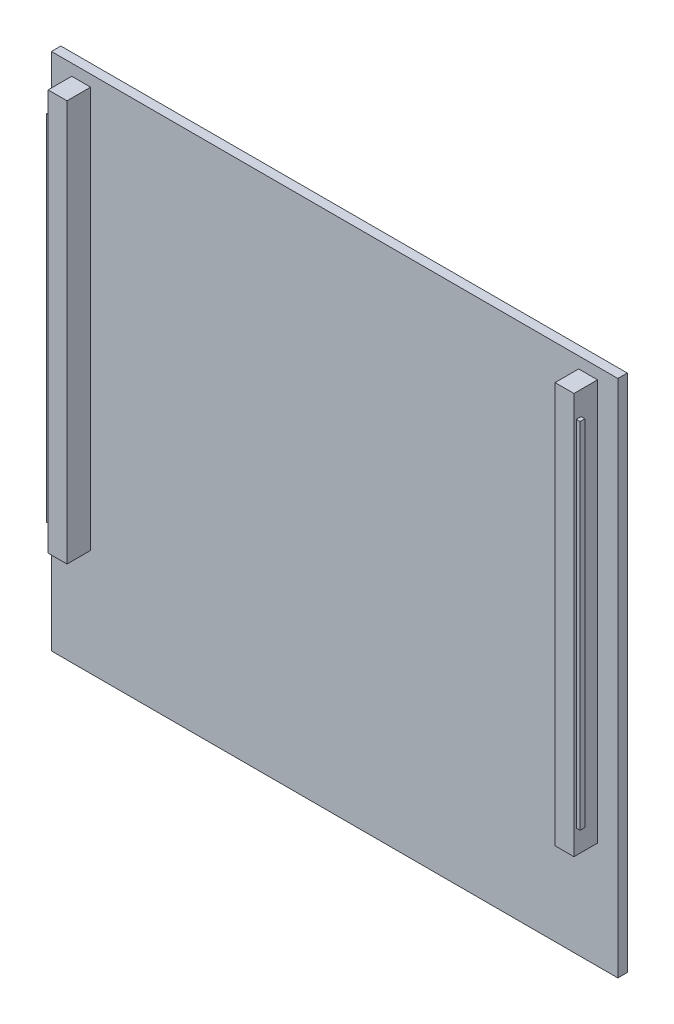
SolidWorks part; units mm, degrees
ref_plane "Ebene vorne" through (0, 0, 0) normal (0, 0, 1) x (1, 0, 0)
ref_plane "Ebene oben" through (0, 0, 0) normal (0, 1, 0) x (1, 0, 0)
ref_plane "Ebene rechts" through (0, 0, 0) normal (1, 0, 0) x (0, 0, -1)
sketch "Skizze1" plane through (0, 0, 0) normal (0, 0, 1) x (1, 0, 0)
  line L1 (-57.6339, 56.1305) -> (62.3661, 56.1305)
  line L2 (-57.6339, 56.1305) -> (-57.6339, -53.8695)
  line L3 (-57.6339, -53.8695) -> (62.3661, -53.8695)
  line L4 (62.3661, 56.1305) -> (62.3661, -53.8695)
  dimension "D1" = 120
  dimension "D2" = 110
extrude "Aufsatz-Linear austragen1" add sketch "Skizze1" along normal blind 2
sketch "Skizze2" plane through (0, 0, 2) normal (0, 0, 1) x (1, 0, 0)
  line L0 (62.3661, 56.1305) -> (-57.6339, 56.1305) construction
  line L1 (-53.3339, 53.7305) -> (-49.3339, 53.7305)
  line L2 (-53.3339, 53.7305) -> (-53.3339, -31.2695)
  line L3 (-53.3339, -31.2695) -> (-49.3339, -31.2695)
  line L4 (-49.3339, 53.7305) -> (-49.3339, -31.2695)
  line L5 (58.0661, 53.7305) -> (54.0661, 53.7305)
  line L6 (58.0661, 53.7305) -> (58.0661, -31.2695)
  line L7 (58.0661, -31.2695) -> (54.0661, -31.2695)
  line L8 (54.0661, 53.7305) -> (54.0661, -31.2695)
  line L9 (-57.6339, 56.1305) -> (-57.6339, -53.8695) construction
  line L10 (62.3661, -53.8695) -> (62.3661, 56.1305) construction
  dimension "D1" = 2.4
  dimension "D2" = 2.4
  dimension "D3" = 85
  dimension "D4" = 85
  dimension "D5" = 4
  dimension "D6" = 4
  dimension "D7" = 4.3
  dimension "D8" = 4.3
extrude "Aufsatz-Linear austragen2" add sketch "Skizze2" along normal blind 5
sketch "Skizze3" plane through (58.0661, 0, 0) normal (1, 0, 0) x (0, 0, -1)
  line L0 (-7, -31.2695) -> (-7, 53.7305) construction
  line L1 (-6.5, 48.7305) -> (-5.5, 48.7305)
  line L2 (-6.5, 48.7305) -> (-6.5, -26.2695)
  line L3 (-6.5, -26.2695) -> (-5.5, -26.2695)
  line L4 (-5.5, 48.7305) -> (-5.5, -26.2695)
  line L5 (-7, 53.7305) -> (-2, 53.7305) construction
  dimension "D1" = 1
  dimension "D2" = 0.5
  dimension "D3" = 5
  dimension "D4" = 75
extrude "Aufsatz-Linear austragen3" add sketch "Skizze3" along normal blind 0.8
sketch "Skizze4" plane through (-53.3339, 0, 0) normal (-1, 0, 0) x (0, 0, 1)
  line L0 (7, 53.7305) -> (7, -31.2695) construction
  line L1 (5.5, 48.7305) -> (6.5, 48.7305)
  line L2 (5.5, 48.7305) -> (5.5, -26.2695)
  line L3 (5.5, -26.2695) -> (6.5, -26.2695)
  line L4 (6.5, 48.7305) -> (6.5, -26.2695)
  line L5 (7, 53.7305) -> (2, 53.7305) construction
  dimension "D1" = 0.5
  dimension "D2" = 1
  dimension "D3" = 5
  dimension "D4" = 75
extrude "Aufsatz-Linear austragen4" add sketch "Skizze4" along normal blind 0.8
